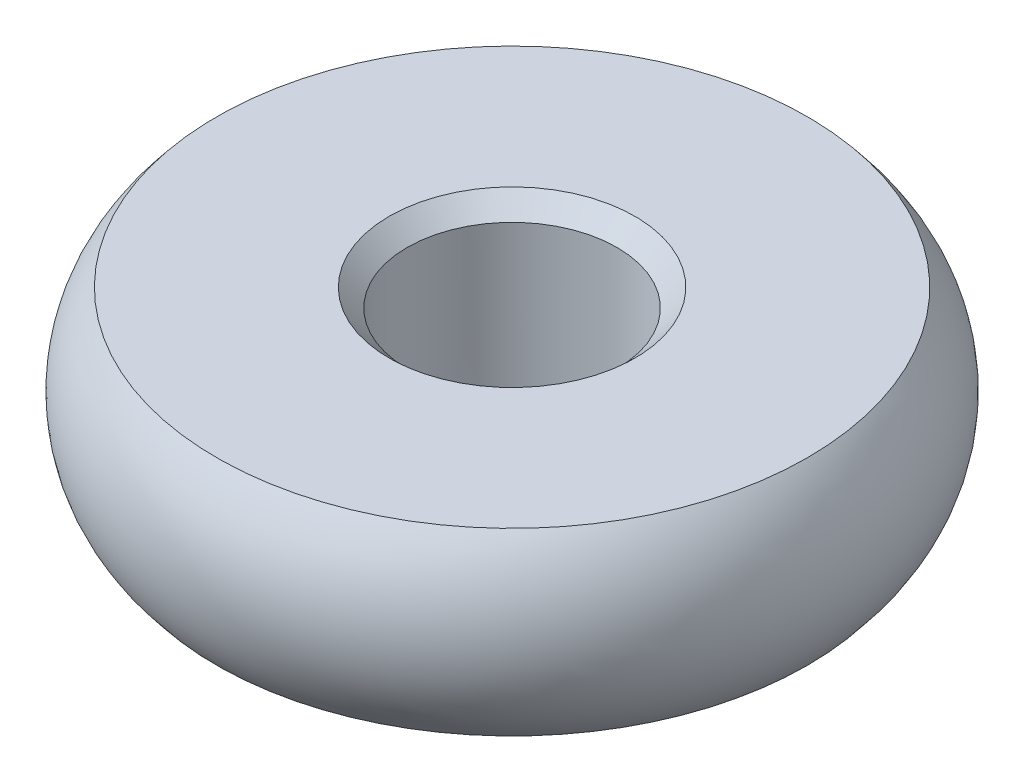
SolidWorks part; units mm, degrees
material "Custom Plastic"
ref_plane "Front Plane" through (0, 0, 0) normal (0, 0, 1) x (1, 0, 0)
ref_plane "Top Plane" through (0, 0, 0) normal (0, 1, 0) x (1, 0, 0)
ref_plane "Right Plane" through (0, 0, 0) normal (1, 0, 0) x (0, 0, -1)
sketch "Sketch1" plane through (0, 0, 0) normal (0, 0, 1) x (1, 0, 0)
  line L0 (-860.2315, 0) -> (42151.3415, 0) construction
  line L1 (0, -860.2315) -> (0, 42151.3415) construction
  line L2 (49.2705, 15) -> (17.5, 15)
  line L3 (17.5, 15) -> (17.5, -15)
  line L4 (17.5, -15) -> (49.2705, -15)
  arc A0 (49.2705, 15) -> (49.2705, -15) centre (32.5, 0) cw
  point P7 (17.5, 0)
  point P9 (55, 0)
  dimension "D3" = 22.5
  dimension "D1" = 30
  dimension "D2" = 17.5
  dimension "D4" = 110
revolve "Revolve1" add sketch "Sketch1" angle 360 about L1
chamfer "Chamfer1" distance 3 angle 45 2 edges at (17.5, 15, 0) (17.5, -15, 0)
